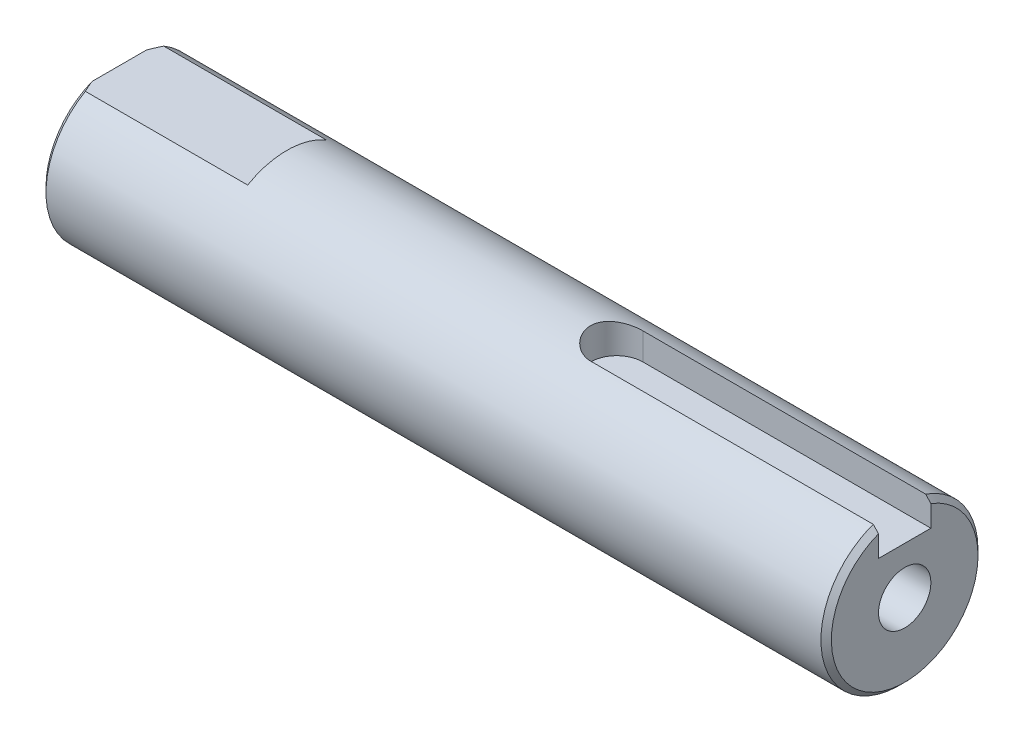
SolidWorks part; units mm, degrees
material "1.4301 (X5CrNi18-10)"
ref_plane "正面" through (0, 0, 0) normal (0, 0, 1) x (1, 0, 0)
ref_plane "平面" through (0, 0, 0) normal (0, 1, 0) x (1, 0, 0)
ref_plane "右側面" through (0, 0, 0) normal (1, 0, 0) x (0, 0, -1)
sketch "ｽｹｯﾁ2" plane through (0, 0, 0) normal (0, 0, 1) x (1, 0, 0)
  line L0 (0, 0) -> (50000, 0) construction
  line L1 (0, 0) -> (0, 7.5)
  line L2 (0, 7.5) -> (75, 7.5)
  line L3 (75, 7.5) -> (75, 0)
  line L4 (75, 0) -> (0, 0)
  dimension "D1" = 15
  dimension "D2" = 75
revolve "回転1" add sketch "ｽｹｯﾁ2" angle 360 about L0
sketch "ｽｹｯﾁ3" plane through (0, 0, 0) normal (0, 1, 0) x (1, 0, 0)
  line L0 (0, 0) -> (-50000, 0) construction
  line L1 (47.5, 2.5) -> (75, 2.5)
  line L2 (75, -7.5) -> (75, 7.5) construction
  line L3 (75, 2.5) -> (75, -2.5)
  line L4 (75, -2.5) -> (47.5, -2.5)
  arc A0 (47.5, 2.5) -> (47.5, -2.5) centre (47.5, 0) ccw
  dimension "D1" = 5
  dimension "D2" = 30
extrude "ｶｯﾄ - 押し出し1" cut sketch "ｽｹｯﾁ3" along normal through all from offset 4.5
sketch "ｽｹｯﾁ4" plane through (0, 0, 0) normal (0, 0, 1) x (1, 0, 0)
  line L0 (0, 0) -> (-50000, 0) construction
  line L1 (0, -7.5) -> (75, -7.5) construction
  line L2 (0, 6.5) -> (16, 6.5)
  line L3 (0, 6.5) -> (0, 7.5)
  line L4 (0, 7.5) -> (16, 7.5)
  line L5 (16, 6.5) -> (16, 7.5)
  line L6 (0, -6.5) -> (16, -6.5)
  line L7 (0, -6.5) -> (0, -7.5)
  line L8 (0, -7.5) -> (16, -7.5)
  line L9 (16, -6.5) -> (16, -7.5)
  dimension "D1" = 13
  dimension "D2" = 16
extrude "ｶｯﾄ - 押し出し2" cut sketch "ｽｹｯﾁ4" against normal through all both and the other way through all
hole_wizard "M5x0.8 ねじ穴1" positions "3Dｽｹｯﾁ2" profile "ｽｹｯﾁ6" tap size "M5x0.8" standard "JIS"
sketch3d "3Dｽｹｯﾁ2"
  point P0 (0, 0, 0)
  point P2 (75, 0, 0)
sketch "ｽｹｯﾁ6" plane through (0, 0, 0) normal (0, 1, 0) x (0, 0, 1)
  line L0 (0, 0) -> (0, 15.2618)
  line L1 (0, 15.2618) -> (2.1, 14)
  line L2 (2.1, 14) -> (2.1, 10)
  line L3 (2.1, 10) -> (2.5, 10)
  line L4 (2.5, 10) -> (2.5, 0)
  line L5 (2.5, 0) -> (0, 0)
  line L10 (0, 15.2618) -> (-2.1, 14) construction
  line L11 (0, -6.35) -> (0, 107.95) construction
  dimension "ねじ下穴ﾄﾞﾘﾙ直径" = 4.2
  dimension "ねじ下穴ﾄﾞﾘﾙの深さ" = 14
  dimension "ねじ山の主要直径" = 5
  dimension "ねじ山の深さ" = 10
  dimension "ﾄﾞﾘﾙ角度" = 118
chamfer "面取り1" distance 0.5 angle 45 3 edges at (75, -7.5, 0) (0, 0, -7.5) (0, 0, 7.5)
